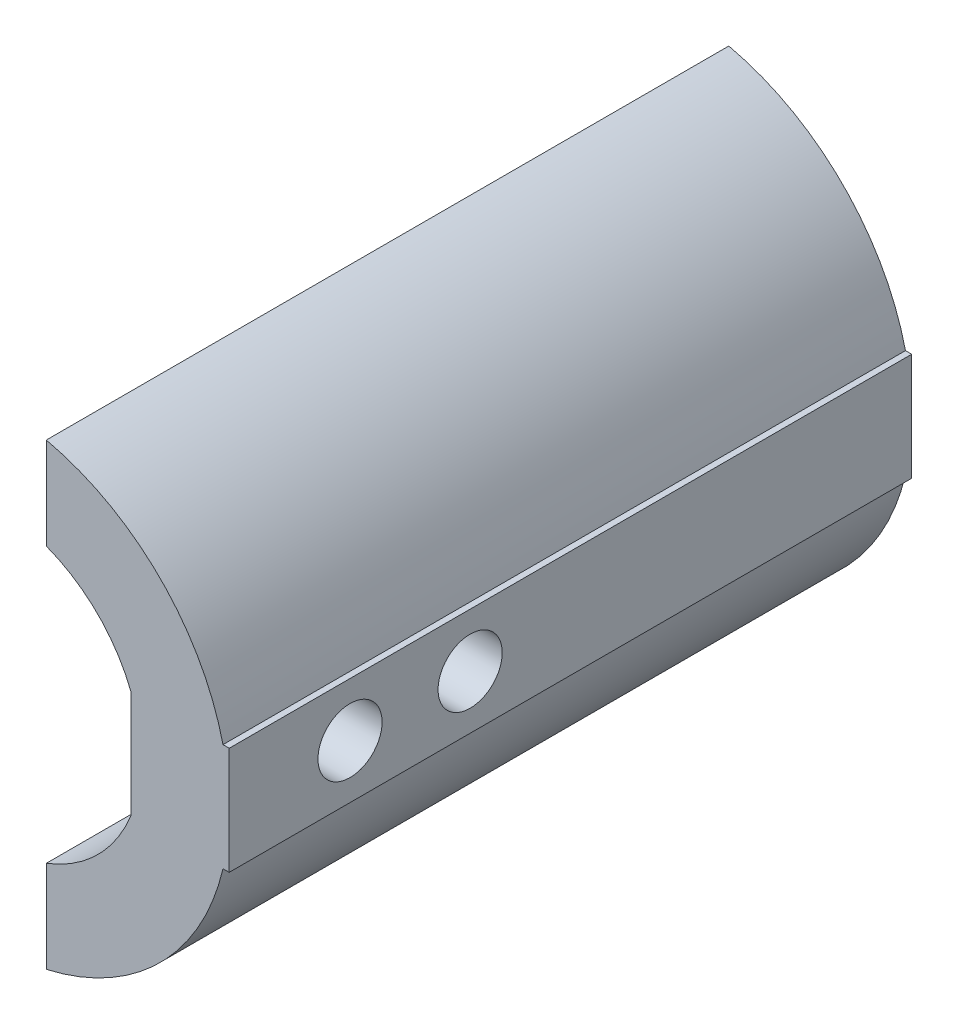
SolidWorks part; units mm, degrees
ref_plane "Front" through (0, 0, 0) normal (0, 0, 1) x (1, 0, 0)
ref_plane "Top" through (0, 0, 0) normal (0, 1, 0) x (1, 0, 0)
ref_plane "Right" through (0, 0, 0) normal (1, 0, 0) x (0, 0, -1)
sketch "Sketch1" plane through (0, 0, 0) normal (0, 0, 1) x (1, 0, 0)
  line L0 (-9.6452, 0) -> (-8.7482, 0) construction
  line L1 (-9.6452, 2) -> (-8.5166, 2) construction
  line L2 (-9.6452, -2) -> (-8.5166, -2) construction
  line L3 (-5.0887, 2) -> (-5.0887, -2)
  line L4 (-8.5166, -2) -> (-8.7482, -2)
  line L5 (-8.7482, -2) -> (-8.7482, 2)
  line L6 (-8.7482, 2) -> (-8.5166, 2)
  line L7 (0, 9.6322) -> (0, -10.6438) construction
  line L8 (8.5166, -2) -> (8.7482, -2)
  line L9 (5.0887, 2) -> (5.0887, -2)
  line L10 (8.7482, -2) -> (8.7482, 2)
  line L11 (8.7482, 2) -> (8.5166, 2)
  line L12 (8.5166, 2) -> (11.0834, 2) construction
  line L13 (8.7482, 0) -> (10.6911, 0) construction
  line L14 (8.5166, -2) -> (11.4454, -2) construction
  line L15 (-5.0887, 2) -> (5.0887, 2) construction
  line L16 (-5.0887, 0) -> (5.4677, 0) construction
  line L17 (-5.0887, -2) -> (5.0887, -2) construction
  arc A0 (5.0887, 2) -> (-5.0887, 2) centre (0, 0) ccw
  arc A1 (8.5166, 2) -> (-8.5166, 2) centre (0, 0) ccw
  arc A2 (-5.0887, -2) -> (5.0887, -2) centre (0, 0) ccw
  arc A3 (-8.5166, -2) -> (8.5166, -2) centre (0, 0) ccw
  dimension "D1" = 2
  dimension "D3" = 10.9353
  dimension "D4" = 17.4965
  dimension "D2" = 2
extrude "Boss-Extrude1" add sketch "Sketch1" against normal blind 25.4
sketch "Sketch2" plane through (0, 0, 0) normal (0, 0, 1) x (1, 0, 0)
  line L1 (-25.4, 9.396) -> (1.9407, 9.396)
  line L2 (-25.4, 9.396) -> (-25.4, -9.9956)
  line L3 (-25.4, -9.9956) -> (1.9407, -9.9956)
  line L4 (1.9407, 9.396) -> (1.9407, -9.9956)
  dimension "D1" = 1.9407
  dimension "D2" = 25.4
  dimension "D3" = 27.3407
  dimension "D4" = 19.3916
extrude "Cut-Extrude1" cut sketch "Sketch2" against normal blind 50
ref_plane "Plane1" through (11.2882, 0, 0) normal (1, 0, 0) x (0, 0, -1)
sketch "Sketch4" plane through (11.2882, 0, 0) normal (1, 0, 0) x (0, 0, -1)
  line L0 (0, -2) -> (0, 2) construction
  circle A0 centre (4.4958, 0) radius 1.1938
  circle A1 centre (8.9662, 0) radius 1.1938
  dimension "D1" = 4.4958
  dimension "D2" = 2.3876
  dimension "D3" = 4.4704
  dimension "D4" = 2.3876
extrude "Cut-Extrude2" cut sketch "Sketch4" against normal blind 50
